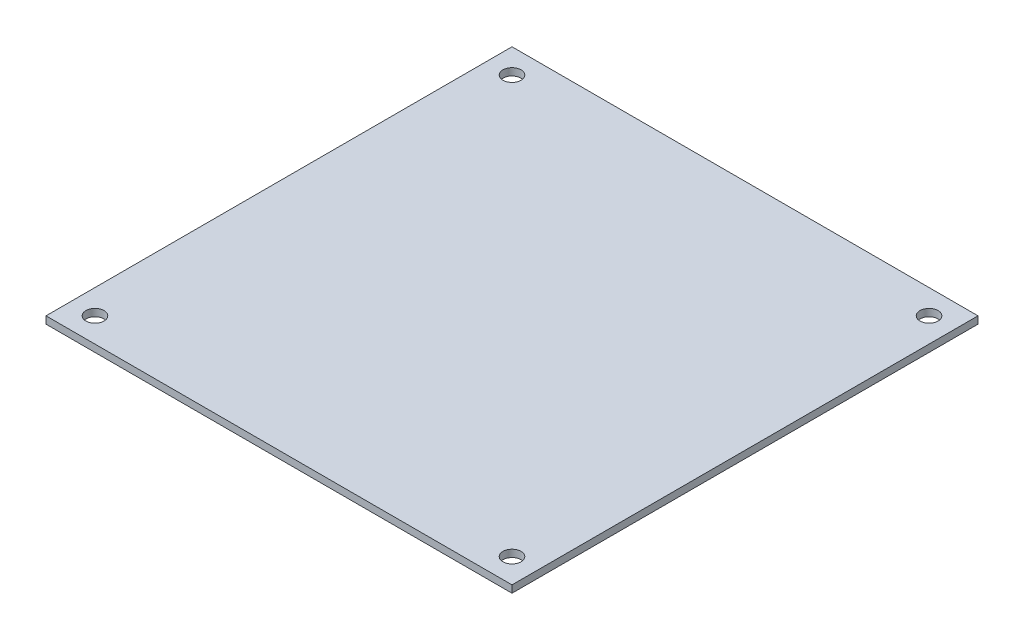
SolidWorks part; units mm, degrees
ref_plane "Front Plane" through (0, 0, 0) normal (0, 0, 1) x (1, 0, 0)
ref_plane "Top Plane" through (0, 0, 0) normal (0, 1, 0) x (1, 0, 0)
ref_plane "Right Plane" through (0, 0, 0) normal (1, 0, 0) x (0, 0, -1)
sketch "Sketch1" plane through (0, 0, 0) normal (0, 1, 0) x (1, 0, 0)
  line L0 (0, 882.8692) -> (0, -849.8686) construction
  line L1 (-642.5, 642.5) -> (642.5, 642.5)
  line L2 (-642.5, 642.5) -> (-642.5, -642.5)
  line L3 (-642.5, -642.5) -> (642.5, -642.5)
  line L4 (642.5, 642.5) -> (642.5, -642.5)
  line L5 (-642.5, 642.5) -> (642.5, -642.5) construction
  line L6 (-642.5, -642.5) -> (642.5, 642.5) construction
  line L7 (-1056.1324, 0) -> (1156.924, 0) construction
  circle A0 centre (-575, 575) radius 25
  circle A1 centre (575, 575) radius 25
  circle A2 centre (575, -575) radius 25
  circle A3 centre (-575, -575) radius 25
  point P0 (0, 0)
  point P12 (0, 0)
  dimension "D2" = 575
  dimension "D3" = 50
  dimension "D1" = 1285
extrude "Boss-Extrude1" add sketch "Sketch1" along normal mid plane 20
